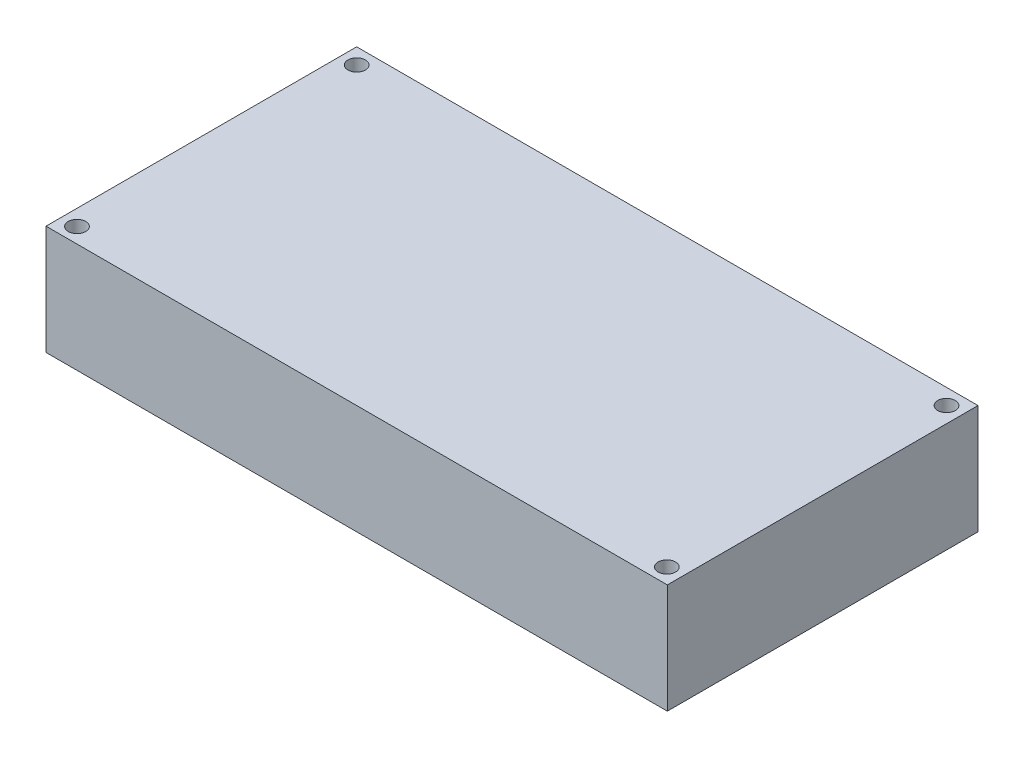
SolidWorks part; units mm, degrees
ref_plane "Front Plane" through (0, 0, 0) normal (0, 0, 1) x (1, 0, 0)
ref_plane "Top Plane" through (0, 0, 0) normal (0, 1, 0) x (1, 0, 0)
ref_plane "Right Plane" through (0, 0, 0) normal (1, 0, 0) x (0, 0, -1)
sketch "Sketch1" plane through (0, 0, 0) normal (0, 1, 0) x (1, 0, 0)
  line L1 (0, 0) -> (142, 0)
  line L2 (0, 0) -> (0, 71)
  line L3 (0, 71) -> (142, 71)
  line L4 (142, 0) -> (142, 71)
  dimension "D1" = 142
  dimension "D2" = 71
extrude "Boss-Extrude1" add sketch "Sketch1" along normal blind 25
sketch "Sketch2" plane through (0, 25, 0) normal (0, 1, 0) x (1, 0, 0)
  line L0 (0, 67.4) -> (11.313, 67.4) construction
  line L1 (0, 71) -> (0, 0) construction
  line L2 (3.6, 71) -> (3.6, 63.8) construction
  line L3 (142, 71) -> (0, 71) construction
  line L4 (0, 35.44) -> (142, 35.44) construction
  line L5 (142, 0) -> (142, 71) construction
  line L6 (0, 0) -> (142, 0) construction
  line L7 (71, 71) -> (71, 0) construction
  circle A0 centre (3.6, 67.4) radius 2
  circle A1 centre (138.4, 67.4) radius 2
  circle A2 centre (138.4, 3.48) radius 2
  circle A3 centre (3.6, 3.48) radius 2
  dimension "D3" = 4
  dimension "D1" = 3.6
  dimension "D2" = 3.6
  dimension "D4" = 35.56
extrude "Cut-Extrude1" cut sketch "Sketch2" against normal through all
